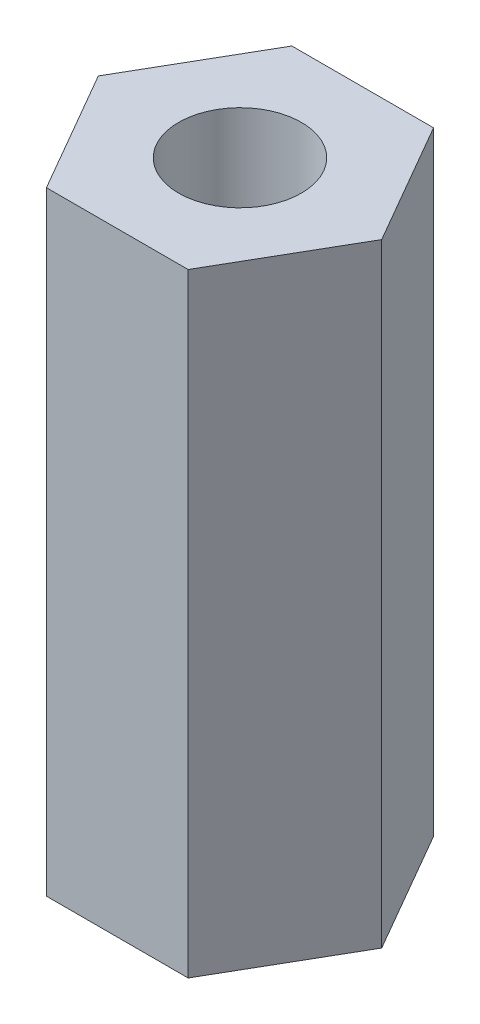
SolidWorks part; units mm, degrees
ref_plane "Front Plane" through (0, 0, 0) normal (0, 0, 1) x (1, 0, 0)
ref_plane "Top Plane" through (0, 0, 0) normal (0, 1, 0) x (1, 0, 0)
ref_plane "Right Plane" through (0, 0, 0) normal (1, 0, 0) x (0, 0, -1)
sketch "Sketch1" plane through (0, 0, 0) normal (0, 1, 0) x (1, 0, 0)
  line L1 (-3.6662, -6.35) -> (3.6662, -6.35)
  line L2 (3.6662, -6.35) -> (7.3323, 0)
  line L3 (7.3323, 0) -> (3.6662, 6.35)
  line L4 (3.6662, 6.35) -> (-3.6662, 6.35)
  line L5 (-3.6662, 6.35) -> (-7.3323, 0)
  line L6 (-7.3323, 0) -> (-3.6662, -6.35)
  circle A0 centre (0, 0) radius 6.35 construction
  circle A1 centre (0, 0) radius 3.175
  dimension "D1" = 12.7
  dimension "D2" = 6.35
extrude "Boss-Extrude1" add sketch "Sketch1" along normal blind 31.75
